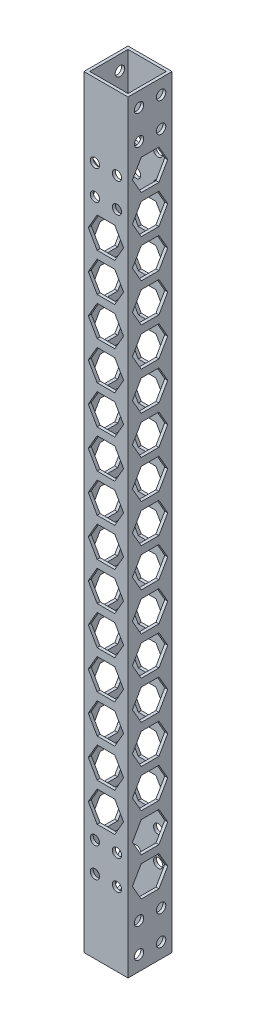
SolidWorks part; units mm, degrees
ref_plane "前视基准面" through (0, 0, 0) normal (0, 0, 1) x (1, 0, 0)
ref_plane "上视基准面" through (0, 0, 0) normal (0, 1, 0) x (1, 0, 0)
ref_plane "右视基准面" through (0, 0, 0) normal (1, 0, 0) x (0, 0, -1)
other "Configuration Table"
sketch "草图1" plane through (0, 0, 0) normal (0, 1, 0) x (1, 0, 0)
  line L1 (6.5, -6.5) -> (-6.5, -6.5)
  line L2 (6.5, -6.5) -> (6.5, 6.5)
  line L3 (6.5, 6.5) -> (-6.5, 6.5)
  line L4 (-6.5, -6.5) -> (-6.5, 6.5)
  line L5 (6.5, -6.5) -> (-6.5, 6.5) construction
  line L6 (6.5, 6.5) -> (-6.5, -6.5) construction
  line L7 (7.5, -7.5) -> (-7.5, -7.5)
  line L8 (7.5, -7.5) -> (7.5, 7.5)
  line L9 (7.5, 7.5) -> (-7.5, 7.5)
  line L10 (-7.5, -7.5) -> (-7.5, 7.5)
  line L11 (7.5, -7.5) -> (-7.5, 7.5) construction
  line L12 (7.5, 7.5) -> (-7.5, -7.5) construction
  point P0 (0, 0)
  point P6 (0, 0)
  dimension "D1" = 15
  dimension "D2" = 13
extrude "凸台-拉伸1" add sketch "草图1" along normal blind 259.4
sketch "草图2" plane through (0, 0, 7.5) normal (0, 0, 1) x (1, 0, 0)
  line L0 (0, 804.3358) -> (0, 762.8538) construction
  line L1 (-7.5, 229.4) -> (7.5, 229.4) construction
  line L2 (-7.5, 259.4) -> (-7.5, 0) construction
  line L3 (7.5, 259.4) -> (7.5, 0) construction
  line L4 (-7.5, 259.4) -> (7.5, 259.4) construction
  line L5 (-7.5, 129.7) -> (7.5, 129.7) construction
  line L6 (-7.5, 30) -> (7.5, 30) construction
  line L7 (3, 206.4) -> (-3, 206.4)
  line L8 (-3, 219.4) -> (-6, 214.2038)
  line L9 (-6, 214.2038) -> (-3, 209.0077)
  line L10 (-3, 209.0077) -> (3, 209.0077)
  line L11 (3, 209.0077) -> (6, 214.2038)
  line L12 (6, 214.2038) -> (3, 219.4)
  line L13 (3, 219.4) -> (-3, 219.4)
  line L14 (6, 201.2038) -> (3, 206.4)
  line L15 (3, 196.0077) -> (6, 201.2038)
  line L16 (-3, 196.0077) -> (3, 196.0077)
  line L17 (-6, 201.2038) -> (-3, 196.0077)
  line L18 (-3, 206.4) -> (-6, 201.2038)
  line L19 (3, 193.4) -> (-3, 193.4)
  line L20 (6, 188.2038) -> (3, 193.4)
  line L21 (3, 183.0077) -> (6, 188.2038)
  line L22 (-3, 183.0077) -> (3, 183.0077)
  line L23 (-6, 188.2038) -> (-3, 183.0077)
  line L24 (-3, 193.4) -> (-6, 188.2038)
  line L25 (3, 180.4) -> (-3, 180.4)
  line L26 (6, 175.2038) -> (3, 180.4)
  line L27 (3, 170.0077) -> (6, 175.2038)
  line L28 (-3, 170.0077) -> (3, 170.0077)
  line L29 (-6, 175.2038) -> (-3, 170.0077)
  line L30 (-3, 180.4) -> (-6, 175.2038)
  line L31 (3, 167.4) -> (-3, 167.4)
  line L32 (6, 162.2038) -> (3, 167.4)
  line L33 (3, 157.0077) -> (6, 162.2038)
  line L34 (-3, 157.0077) -> (3, 157.0077)
  line L35 (-6, 162.2038) -> (-3, 157.0077)
  line L36 (-3, 167.4) -> (-6, 162.2038)
  line L37 (3, 154.4) -> (-3, 154.4)
  line L38 (6, 149.2038) -> (3, 154.4)
  line L39 (3, 144.0077) -> (6, 149.2038)
  line L40 (-3, 144.0077) -> (3, 144.0077)
  line L41 (-6, 149.2038) -> (-3, 144.0077)
  line L42 (-3, 154.4) -> (-6, 149.2038)
  line L43 (3, 141.4) -> (-3, 141.4)
  line L44 (6, 136.2038) -> (3, 141.4)
  line L45 (3, 131.0077) -> (6, 136.2038)
  line L46 (-3, 131.0077) -> (3, 131.0077)
  line L47 (-6, 136.2038) -> (-3, 131.0077)
  line L48 (-3, 141.4) -> (-6, 136.2038)
  line L49 (3, 128.4) -> (-3, 128.4)
  line L50 (6, 123.2038) -> (3, 128.4)
  line L51 (3, 118.0077) -> (6, 123.2038)
  line L52 (-3, 118.0077) -> (3, 118.0077)
  line L53 (-6, 123.2038) -> (-3, 118.0077)
  line L54 (-3, 128.4) -> (-6, 123.2038)
  line L55 (3, 115.4) -> (-3, 115.4)
  line L56 (6, 110.2038) -> (3, 115.4)
  line L57 (3, 105.0077) -> (6, 110.2038)
  line L58 (-3, 105.0077) -> (3, 105.0077)
  line L59 (-6, 110.2038) -> (-3, 105.0077)
  line L60 (-3, 115.4) -> (-6, 110.2038)
  line L61 (3, 102.4) -> (-3, 102.4)
  line L62 (6, 97.2038) -> (3, 102.4)
  line L63 (3, 92.0077) -> (6, 97.2038)
  line L64 (-3, 92.0077) -> (3, 92.0077)
  line L65 (-6, 97.2038) -> (-3, 92.0077)
  line L66 (-3, 102.4) -> (-6, 97.2038)
  line L67 (3, 89.4) -> (-3, 89.4)
  line L68 (6, 84.2038) -> (3, 89.4)
  line L69 (3, 79.0077) -> (6, 84.2038)
  line L70 (-3, 79.0077) -> (3, 79.0077)
  line L71 (-6, 84.2038) -> (-3, 79.0077)
  line L72 (-3, 89.4) -> (-6, 84.2038)
  line L73 (3, 76.4) -> (-3, 76.4)
  line L74 (6, 71.2038) -> (3, 76.4)
  line L75 (3, 66.0077) -> (6, 71.2038)
  line L76 (-3, 66.0077) -> (3, 66.0077)
  line L77 (-6, 71.2038) -> (-3, 66.0077)
  line L78 (-3, 76.4) -> (-6, 71.2038)
  line L79 (3, 63.4) -> (-3, 63.4)
  line L80 (6, 58.2038) -> (3, 63.4)
  line L81 (3, 53.0077) -> (6, 58.2038)
  line L82 (-3, 53.0077) -> (3, 53.0077)
  line L83 (-6, 58.2038) -> (-3, 53.0077)
  line L84 (-3, 63.4) -> (-6, 58.2038)
  line L85 (3, 50.4) -> (-3, 50.4)
  line L86 (6, 45.2038) -> (3, 50.4)
  line L87 (3, 40.0077) -> (6, 45.2038)
  line L88 (-3, 40.0077) -> (3, 40.0077)
  line L89 (-6, 45.2038) -> (-3, 40.0077)
  line L90 (-3, 50.4) -> (-6, 45.2038)
  circle A0 centre (-3.75, 234.4) radius 1.575
  circle A1 centre (3.75, 234.4) radius 1.575
  circle A2 centre (-3.75, 224.4) radius 1.575
  circle A3 centre (3.75, 224.4) radius 1.575
  circle A4 centre (3.75, 35) radius 1.575
  circle A5 centre (-3.75, 35) radius 1.575
  circle A6 centre (3.75, 25) radius 1.575
  circle A7 centre (-3.75, 25) radius 1.575
  circle A8 centre (0, 214.2038) radius 5.1962 construction
  dimension "D2" = 3.15
  dimension "D5" = 6
  dimension "D8" = 13
  dimension "D1" = 30
  dimension "D3" = 7.5
  dimension "D4" = 10
  dimension "D6" = 10
  dimension "D7" = 14
extrude "切除-拉伸1" cut sketch "草图2" against normal up to surface (15 mm away) up to face at (0, 129.7, -7.5)
sketch "草图3" plane through (-7.5, 0, 0) normal (-1, 0, 0) x (0, 0, 1)
  line L0 (0, 809.7886) -> (0, 782.9032) construction
  line L1 (-7.5, 249.4) -> (7.5, 249.4) construction
  line L2 (-7.5, 259.4) -> (-7.5, 0) construction
  line L3 (7.5, 259.4) -> (7.5, 0) construction
  line L4 (-7.5, 259.4) -> (7.5, 259.4) construction
  line L5 (7.5, 129.7) -> (-7.5, 129.7) construction
  line L6 (-7.5, 10) -> (7.5, 10) construction
  line L7 (3, 226.4) -> (-3, 226.4)
  line L8 (-3, 239.4) -> (-6, 234.2038)
  line L9 (-6, 234.2038) -> (-3, 229.0077)
  line L10 (-3, 229.0077) -> (3, 229.0077)
  line L11 (3, 229.0077) -> (6, 234.2038)
  line L12 (6, 234.2038) -> (3, 239.4)
  line L13 (3, 239.4) -> (-3, 239.4)
  line L14 (6, 221.2038) -> (3, 226.4)
  line L15 (3, 216.0077) -> (6, 221.2038)
  line L16 (-3, 216.0077) -> (3, 216.0077)
  line L17 (-6, 221.2038) -> (-3, 216.0077)
  line L18 (-3, 226.4) -> (-6, 221.2038)
  line L19 (3, 213.4) -> (-3, 213.4)
  line L20 (6, 208.2038) -> (3, 213.4)
  line L21 (3, 203.0077) -> (6, 208.2038)
  line L22 (-3, 203.0077) -> (3, 203.0077)
  line L23 (-6, 208.2038) -> (-3, 203.0077)
  line L24 (-3, 213.4) -> (-6, 208.2038)
  line L25 (3, 200.4) -> (-3, 200.4)
  line L26 (6, 195.2038) -> (3, 200.4)
  line L27 (3, 190.0077) -> (6, 195.2038)
  line L28 (-3, 190.0077) -> (3, 190.0077)
  line L29 (-6, 195.2038) -> (-3, 190.0077)
  line L30 (-3, 200.4) -> (-6, 195.2038)
  line L31 (3, 187.4) -> (-3, 187.4)
  line L32 (6, 182.2038) -> (3, 187.4)
  line L33 (3, 177.0077) -> (6, 182.2038)
  line L34 (-3, 177.0077) -> (3, 177.0077)
  line L35 (-6, 182.2038) -> (-3, 177.0077)
  line L36 (-3, 187.4) -> (-6, 182.2038)
  line L37 (3, 174.4) -> (-3, 174.4)
  line L38 (6, 169.2038) -> (3, 174.4)
  line L39 (3, 164.0077) -> (6, 169.2038)
  line L40 (-3, 164.0077) -> (3, 164.0077)
  line L41 (-6, 169.2038) -> (-3, 164.0077)
  line L42 (-3, 174.4) -> (-6, 169.2038)
  line L43 (3, 161.4) -> (-3, 161.4)
  line L44 (6, 156.2038) -> (3, 161.4)
  line L45 (3, 151.0077) -> (6, 156.2038)
  line L46 (-3, 151.0077) -> (3, 151.0077)
  line L47 (-6, 156.2038) -> (-3, 151.0077)
  line L48 (-3, 161.4) -> (-6, 156.2038)
  line L49 (3, 148.4) -> (-3, 148.4)
  line L50 (6, 143.2038) -> (3, 148.4)
  line L51 (3, 138.0077) -> (6, 143.2038)
  line L52 (-3, 138.0077) -> (3, 138.0077)
  line L53 (-6, 143.2038) -> (-3, 138.0077)
  line L54 (-3, 148.4) -> (-6, 143.2038)
  line L55 (3, 135.4) -> (-3, 135.4)
  line L56 (6, 130.2038) -> (3, 135.4)
  line L57 (3, 125.0077) -> (6, 130.2038)
  line L58 (-3, 125.0077) -> (3, 125.0077)
  line L59 (-6, 130.2038) -> (-3, 125.0077)
  line L60 (-3, 135.4) -> (-6, 130.2038)
  line L61 (3, 122.4) -> (-3, 122.4)
  line L62 (6, 117.2038) -> (3, 122.4)
  line L63 (3, 112.0077) -> (6, 117.2038)
  line L64 (-3, 112.0077) -> (3, 112.0077)
  line L65 (-6, 117.2038) -> (-3, 112.0077)
  line L66 (-3, 122.4) -> (-6, 117.2038)
  line L67 (3, 109.4) -> (-3, 109.4)
  line L68 (6, 104.2038) -> (3, 109.4)
  line L69 (3, 99.0077) -> (6, 104.2038)
  line L70 (-3, 99.0077) -> (3, 99.0077)
  line L71 (-6, 104.2038) -> (-3, 99.0077)
  line L72 (-3, 109.4) -> (-6, 104.2038)
  line L73 (3, 96.4) -> (-3, 96.4)
  line L74 (6, 91.2038) -> (3, 96.4)
  line L75 (3, 86.0077) -> (6, 91.2038)
  line L76 (-3, 86.0077) -> (3, 86.0077)
  line L77 (-6, 91.2038) -> (-3, 86.0077)
  line L78 (-3, 96.4) -> (-6, 91.2038)
  line L79 (3, 83.4) -> (-3, 83.4)
  line L80 (6, 78.2038) -> (3, 83.4)
  line L81 (3, 73.0077) -> (6, 78.2038)
  line L82 (-3, 73.0077) -> (3, 73.0077)
  line L83 (-6, 78.2038) -> (-3, 73.0077)
  line L84 (-3, 83.4) -> (-6, 78.2038)
  line L85 (3, 70.4) -> (-3, 70.4)
  line L86 (6, 65.2038) -> (3, 70.4)
  line L87 (3, 60.0077) -> (6, 65.2038)
  line L88 (-3, 60.0077) -> (3, 60.0077)
  line L89 (-6, 65.2038) -> (-3, 60.0077)
  line L90 (-3, 70.4) -> (-6, 65.2038)
  line L91 (3, 57.4) -> (-3, 57.4)
  line L92 (6, 52.2038) -> (3, 57.4)
  line L93 (3, 47.0077) -> (6, 52.2038)
  line L94 (-3, 47.0077) -> (3, 47.0077)
  line L95 (-6, 52.2038) -> (-3, 47.0077)
  line L96 (-3, 57.4) -> (-6, 52.2038)
  line L97 (3, 44.4) -> (-3, 44.4)
  line L98 (6, 39.2038) -> (3, 44.4)
  line L99 (3, 34.0077) -> (6, 39.2038)
  line L100 (-3, 34.0077) -> (3, 34.0077)
  line L101 (-6, 39.2038) -> (-3, 34.0077)
  line L102 (-3, 44.4) -> (-6, 39.2038)
  line L103 (3, 31.4) -> (-3, 31.4)
  line L104 (6, 26.2038) -> (3, 31.4)
  line L105 (3, 21.0077) -> (6, 26.2038)
  line L106 (-3, 21.0077) -> (3, 21.0077)
  line L107 (-6, 26.2038) -> (-3, 21.0077)
  line L108 (-3, 31.4) -> (-6, 26.2038)
  circle A0 centre (-3.75, 254.4) radius 1.6
  circle A1 centre (3.75, 254.4) radius 1.6
  circle A2 centre (-3.75, 244.4) radius 1.6
  circle A3 centre (3.75, 244.4) radius 1.6
  circle A4 centre (3.75, 15) radius 1.6
  circle A5 centre (-3.75, 15) radius 1.6
  circle A6 centre (3.75, 5) radius 1.6
  circle A7 centre (-3.75, 5) radius 1.6
  circle A8 centre (0, 234.2038) radius 5.1962 construction
  dimension "D2" = 3.2
  dimension "D5" = 6
  dimension "D1" = 10
  dimension "D3" = 7.5
  dimension "D4" = 10
  dimension "D6" = 10
  dimension "D8" = 13
  dimension "D7" = 17
extrude "切除-拉伸2" cut sketch "草图3" against normal up to surface (15 mm away) up to face at (7.5, 129.7, 0)
